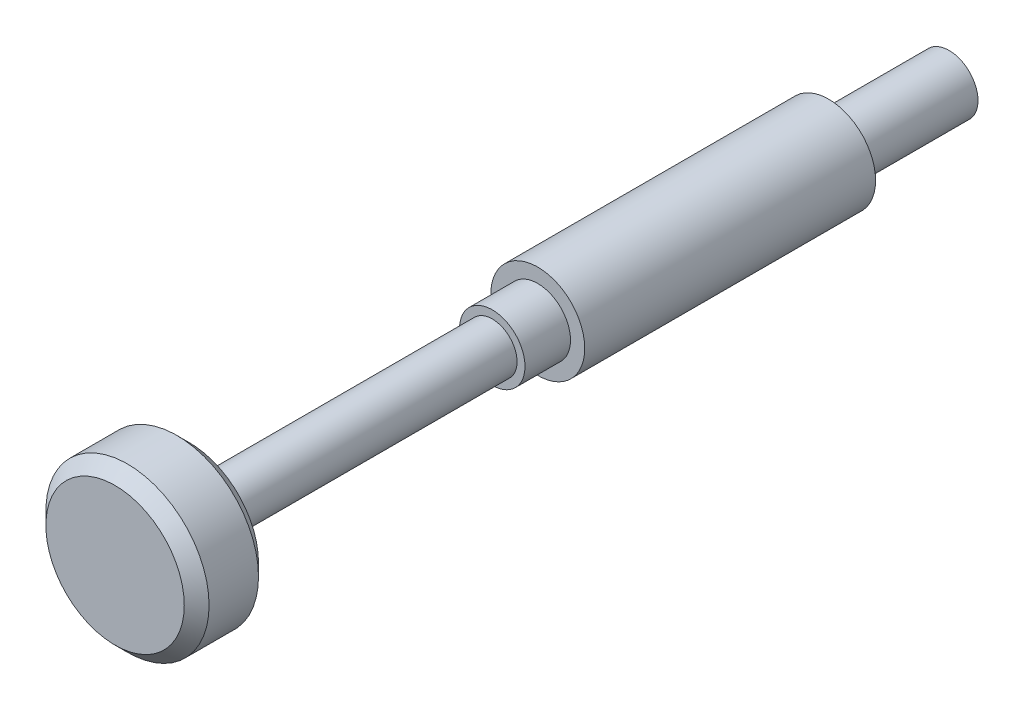
SolidWorks part; units mm, degrees
ref_plane "Front" through (0, 0, 0) normal (0, 0, 1) x (1, 0, 0)
ref_plane "Top" through (0, 0, 0) normal (0, 1, 0) x (1, 0, 0)
ref_plane "Right" through (0, 0, 0) normal (1, 0, 0) x (0, 0, -1)
sketch "Sketch1" plane through (0, 0, 0) normal (0, 0, 1) x (1, 0, 0)
  circle A0 centre (0, 0) radius 3.5
  dimension "D1" = 7
extrude "Boss-Extrude1" add sketch "Sketch1" along normal blind 14.55
sketch "Sketch2" plane through (0, 0, 14.55) normal (0, 0, 1) x (1, 0, 0)
  circle A0 centre (0, 0) radius 5.675
  dimension "D1" = 11.35
extrude "Boss-Extrude2" add sketch "Sketch2" along normal blind 35.14
sketch "Sketch3" plane through (0, 0, 49.69) normal (0, 0, 1) x (1, 0, 0)
  circle A0 centre (0, 0) radius 3.955
  dimension "D1" = 7.91
extrude "Boss-Extrude3" add sketch "Sketch3" along normal blind 5.5
sketch "Sketch4" plane through (0, 0, 55.19) normal (0, 0, 1) x (1, 0, 0)
  circle A0 centre (0, 0) radius 3
  dimension "D1" = 6
extrude "Boss-Extrude4" add sketch "Sketch4" along normal blind 36.6
sketch "Sketch5" plane through (0, 0, 91.79) normal (0, 0, 1) x (1, 0, 0)
  circle A0 centre (0, 0) radius 9.86
  dimension "D1" = 19.72
extrude "Boss-Extrude5" add sketch "Sketch5" along normal offset from surface (8.97 mm away) 100.76 up to face at (3.5, 0, 0)
chamfer "Chamfer1" distance 1.5 angle 45 2 edges at (9.86, 0, 100.76) (9.86, 0, 91.79)
